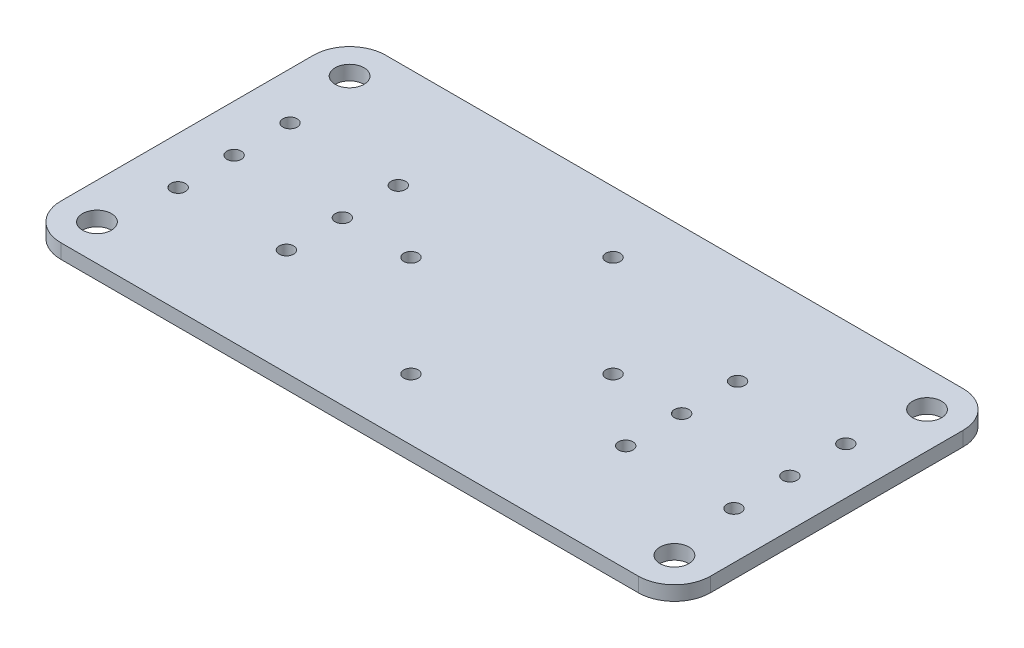
SolidWorks part; units mm, degrees
ref_plane "Alzado" through (0, 0, 0) normal (0, 0, 1) x (1, 0, 0)
ref_plane "Planta" through (0, 0, 0) normal (0, 1, 0) x (1, 0, 0)
ref_plane "Vista lateral" through (0, 0, 0) normal (1, 0, 0) x (0, 0, -1)
sketch "Croquis2" plane through (0, 0, 0) normal (0, 1, 0) x (1, 0, 0)
  line L1 (-90, -45) -> (90, -45)
  line L2 (-90, -45) -> (-90, 45)
  line L3 (-90, 45) -> (90, 45)
  line L4 (90, -45) -> (90, 45)
  line L5 (-90, -45) -> (90, 45) construction
  line L6 (-90, 45) -> (90, -45) construction
  point P0 (0, 0)
  dimension "D1" = 90
  dimension "D2" = 180
extrude "Saliente-Extruir1" add sketch "Croquis2" along normal blind 4
fillet "Redondeo1" radius 10 4 edges at (90, 2, 45) (90, 2, -45) (-90, 2, -45) (-90, 2, 45)
sketch "Croquis4" plane through (0, 4, 0) normal (0, 1, 0) x (1, 0, 0)
  line L0 (0, 0) -> (0, 59.7635) construction
  circle A0 centre (-80, 35) radius 4
  circle A1 centre (-80, -35) radius 4
  circle A4 centre (80, -35) radius 4
  circle A5 centre (80, 35) radius 4
  dimension "D1" = 8
sketch "Croquis8" plane through (0, 4, 0) normal (0, 1, 0) x (1, 0, 0)
  line L0 (0, 0) -> (-90, 0) construction
  line L2 (0, 0) -> (0, 45) construction
  line L3 (-90, 35) -> (-90, -35) construction
  line L4 (80, 45) -> (-80, 45) construction
  circle A2 centre (-47, 0) radius 2
  circle A4 centre (-77, 0) radius 2
  circle A7 centre (77, 0) radius 2
  circle A9 centre (47, 0) radius 2
  circle A10 centre (-77, 15.5) radius 2
  circle A11 centre (-47, 15.5) radius 2
  circle A12 centre (-77, -15.5) radius 2
  circle A13 centre (-47, -15.5) radius 2
  circle A14 centre (47, -15.5) radius 2
  circle A15 centre (77, -15.5) radius 2
  circle A16 centre (77, 15.5) radius 2
  circle A17 centre (47, 15.5) radius 2
  dimension "D1" = 13
  dimension "D2" = 45
  dimension "D3" = 30
  dimension "D4" = 4
  dimension "D5" = 15.5
extrude "Cortar-Extruir1" cut sketch "Croquis8" against normal up to next
extrude "Cortar-Extruir2" cut sketch "Croquis4" against normal up to next
sketch "Croquis9" plane through (0, 4, 0) normal (0, 1, 0) x (1, 0, 0)
  line L0 (80, 45) -> (-80, 45) construction
  line L1 (0, 0) -> (10.2398, 0) construction
  line L2 (0, 0) -> (0, 12.2878) construction
  circle A0 centre (0, 28) radius 2
  circle A1 centre (-28, 0) radius 2
  circle A2 centre (-47, 0) radius 2 construction
  circle A3 centre (0, -28) radius 2
  circle A4 centre (28, 0) radius 2
  dimension "D3" = 4
  dimension "D4" = 4
  dimension "D1" = 17
  dimension "D2" = 19
extrude "Cortar-Extruir3" cut sketch "Croquis9" against normal through all
